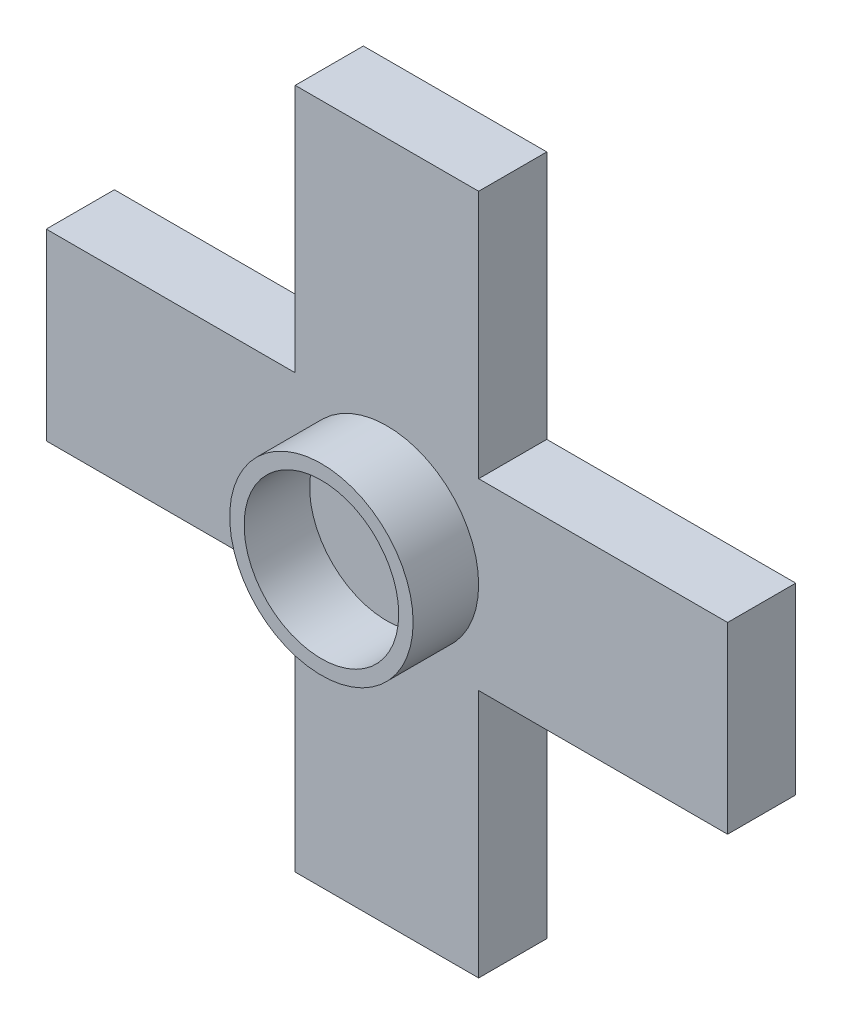
SolidWorks part; units mm, degrees
ref_plane "正面" through (0, 0, 0) normal (0, 0, 1) x (1, 0, 0)
ref_plane "平面" through (0, 0, 0) normal (0, 1, 0) x (1, 0, 0)
ref_plane "右側面" through (0, 0, 0) normal (1, 0, 0) x (0, 0, -1)
sketch "ｽｹｯﾁ1" plane through (0, 0, 0) normal (0, 0, 1) x (1, 0, 0)
  line L0 (11.2984, 0.0786) -> (20.7984, 0.0786)
  line L1 (37.2984, 0.0786) -> (27.7984, 0.0786)
  line L2 (11.2984, 0.0786) -> (11.2984, -6.9214)
  line L3 (37.2984, -6.9214) -> (27.7984, -6.9214)
  line L4 (37.2984, 0.0786) -> (37.2984, -6.9214)
  line L5 (20.7984, 9.5786) -> (27.7984, 9.5786)
  line L6 (20.7984, 9.5786) -> (20.7984, 0.0786)
  line L7 (20.7984, -16.4214) -> (27.7984, -16.4214)
  line L8 (27.7984, 9.5786) -> (27.7984, 0.0786)
  line L9 (11.2984, -6.9214) -> (20.7984, -6.9214)
  line L10 (27.7984, -16.4214) -> (27.7984, -6.9214)
  line L11 (20.7984, -16.4214) -> (20.7984, -6.9214)
  dimension "D1" = 26
  dimension "D2" = 26
  dimension "D3" = 7
  dimension "D6" = 7
extrude "ﾎﾞｽ - 押し出し1" add sketch "ｽｹｯﾁ1" along normal blind 2.6
sketch "ｽｹｯﾁ2" plane through (0, 0, 2.6) normal (0, 0, 1) x (1, 0, 0)
  line L0 (24.2984, -3.4214) -> (27.7984, 0.0786) construction
  line L1 (24.2984, -3.4214) -> (20.7984, -6.9214) construction
  line L2 (24.2984, -3.4214) -> (27.7984, -6.9214) construction
  line L3 (20.7984, 0.0786) -> (24.2984, -3.4214) construction
  circle A0 centre (24.2984, -3.4214) radius 3.5
  circle A1 centre (24.2984, -3.4214) radius 2.95
  dimension "D1" = 5.9
  dimension "D2" = 7
extrude "ﾎﾞｽ - 押し出し2" add sketch "ｽｹｯﾁ2" along normal blind 2.5
